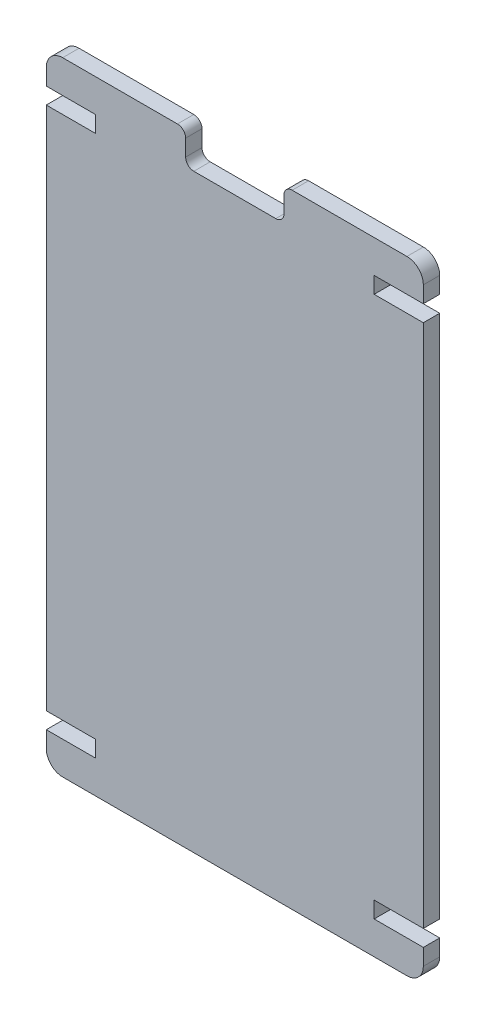
SolidWorks part; units mm, degrees
ref_plane "Front Plane" through (0, 0, 0) normal (0, 0, 1) x (1, 0, 0)
ref_plane "Top Plane" through (0, 0, 0) normal (0, 1, 0) x (1, 0, 0)
ref_plane "Right Plane" through (0, 0, 0) normal (1, 0, 0) x (0, 0, -1)
sketch "Sketch1" plane through (0, 0, 0) normal (0, 0, 1) x (1, 0, 0)
  line L0 (-21, 38) -> (-7, 38)
  line L1 (-23, 36) -> (-23, 34)
  line L2 (23, 36) -> (23, 34)
  line L3 (21, -38) -> (-21, -38)
  line L4 (-23, -34) -> (-17, -34)
  line L5 (-17, -34) -> (-17, -32)
  line L6 (-17, -32) -> (-23, -32)
  line L7 (-23, -34) -> (-23, -36)
  line L8 (-23, 34) -> (-17, 34)
  line L9 (-17, 34) -> (-17, 32)
  line L10 (-17, 32) -> (-23, 32)
  line L11 (-23, 32) -> (-23, -32)
  line L12 (-5, 34) -> (5, 34)
  line L13 (17, -32) -> (23, -32)
  line L14 (17, -34) -> (17, -32)
  line L15 (23, -34) -> (17, -34)
  line L16 (17, 32) -> (23, 32)
  line L17 (17, 34) -> (17, 32)
  line L18 (23, 34) -> (17, 34)
  line L19 (23, 32) -> (23, -32)
  line L20 (23, -34) -> (23, -36)
  line L21 (-6, 35) -> (-6, 37)
  line L22 (6, 35) -> (6, 37)
  line L23 (7, 38) -> (21, 38)
  arc A0 (-23, -36) -> (-21, -38) centre (-21, -36) ccw
  arc A1 (23, -36) -> (21, -38) centre (21, -36) cw
  arc A2 (23, 36) -> (21, 38) centre (21, 36) ccw
  arc A3 (-21, 38) -> (-23, 36) centre (-21, 36) ccw
  arc A4 (-6, 35) -> (-5, 34) centre (-5, 35) ccw
  arc A5 (6, 35) -> (5, 34) centre (5, 35) cw
  arc A6 (7, 38) -> (6, 37) centre (7, 37) ccw
  arc A7 (-6, 37) -> (-7, 38) centre (-7, 37) ccw
  point P24 (-23, -38)
  point P29 (23, 38)
  point P32 (-23, 38)
  point P38 (-6, 34)
  point P41 (6, 34)
  point P44 (6, 38)
  dimension "D11" = 2
  dimension "D14" = 1
  dimension "D1" = 46
  dimension "D2" = 38
  dimension "D3" = 38
  dimension "D4" = 23
  dimension "D5" = 4
  dimension "D6" = 6
  dimension "D7" = 2
  dimension "D8" = 4
  dimension "D9" = 4
  dimension "D10" = 4
  dimension "D12" = 6
  dimension "D13" = 6
extrude "Boss-Extrude1" add sketch "Sketch1" along normal blind 2
